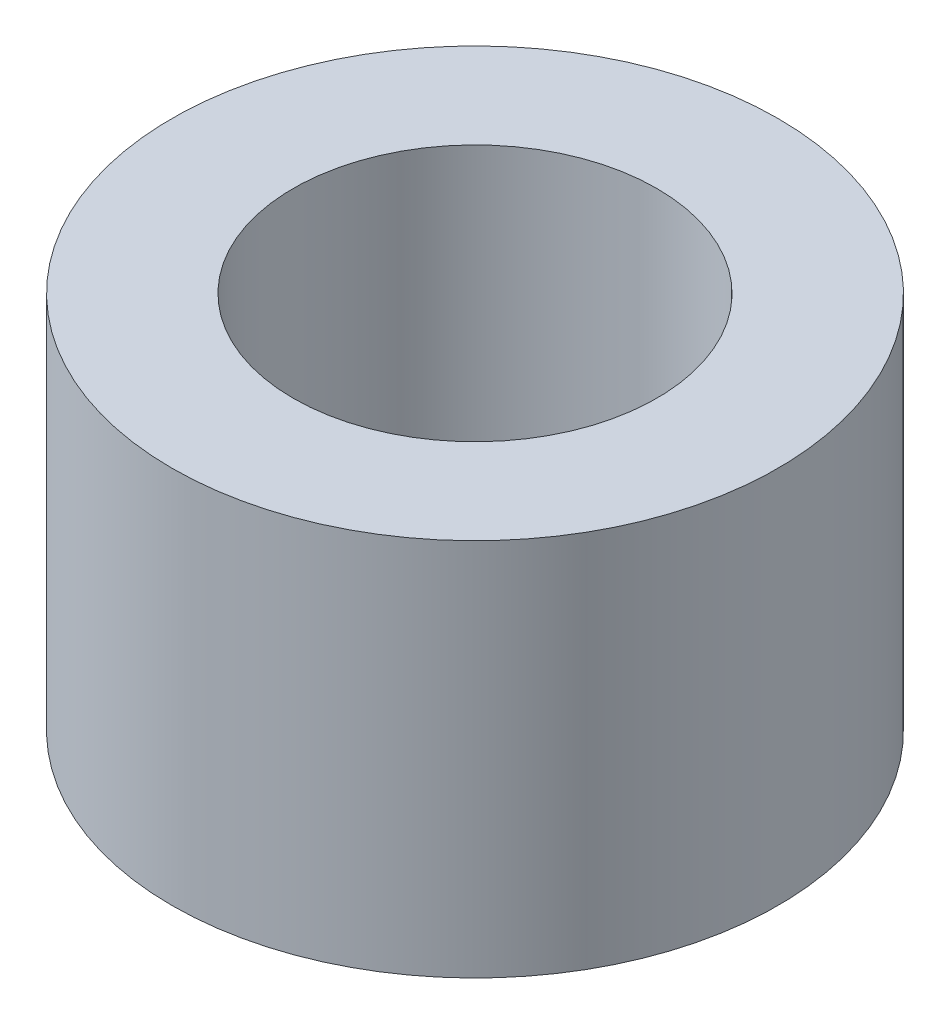
SolidWorks part; units mm, degrees
ref_plane "Plan de face" through (0, 0, 0) normal (0, 0, 1) x (1, 0, 0)
ref_plane "Plan de dessus" through (0, 0, 0) normal (0, 1, 0) x (1, 0, 0)
ref_plane "Plan de droite" through (0, 0, 0) normal (1, 0, 0) x (0, 0, -1)
sketch "Esquisse1" plane through (0, 0, 0) normal (0, 1, 0) x (1, 0, 0)
  line L0 (-1.5672, 0) -> (3.7781, 0) construction
  line L1 (0, 4.9675) -> (0, -3.7361) construction
  circle A0 centre (0, 0) radius 4
  dimension "D1" = 8
extrude "Boss.-Extru.1" add sketch "Esquisse1" along normal blind 5
sketch "Esquisse2" plane through (0, 5, 0) normal (0, 1, 0) x (1, 0, 0)
  line L0 (0, 3.1389) -> (0, -3.2505) construction
  line L1 (-3.1775, 0) -> (3.7357, 0) construction
  line L2 (0, 0) -> (-0.5051, 3.1888) construction
  circle A42 centre (0, 0) radius 2.4
  dimension "D1" = 4.8
  dimension "D3" = 9
sketch "Esquisse3" plane through (0, 0, 0) normal (0, -1, 0) x (1, 0, 0)
  circle A0 centre (0, 0) radius 1.5
  dimension "D1" = 3
extrude "Enlèv. mat.-Extru.2" cut sketch "Esquisse3" against normal through all
extrude "Enlèv. mat.-Extru.3" cut sketch "Esquisse2" against normal blind 4
